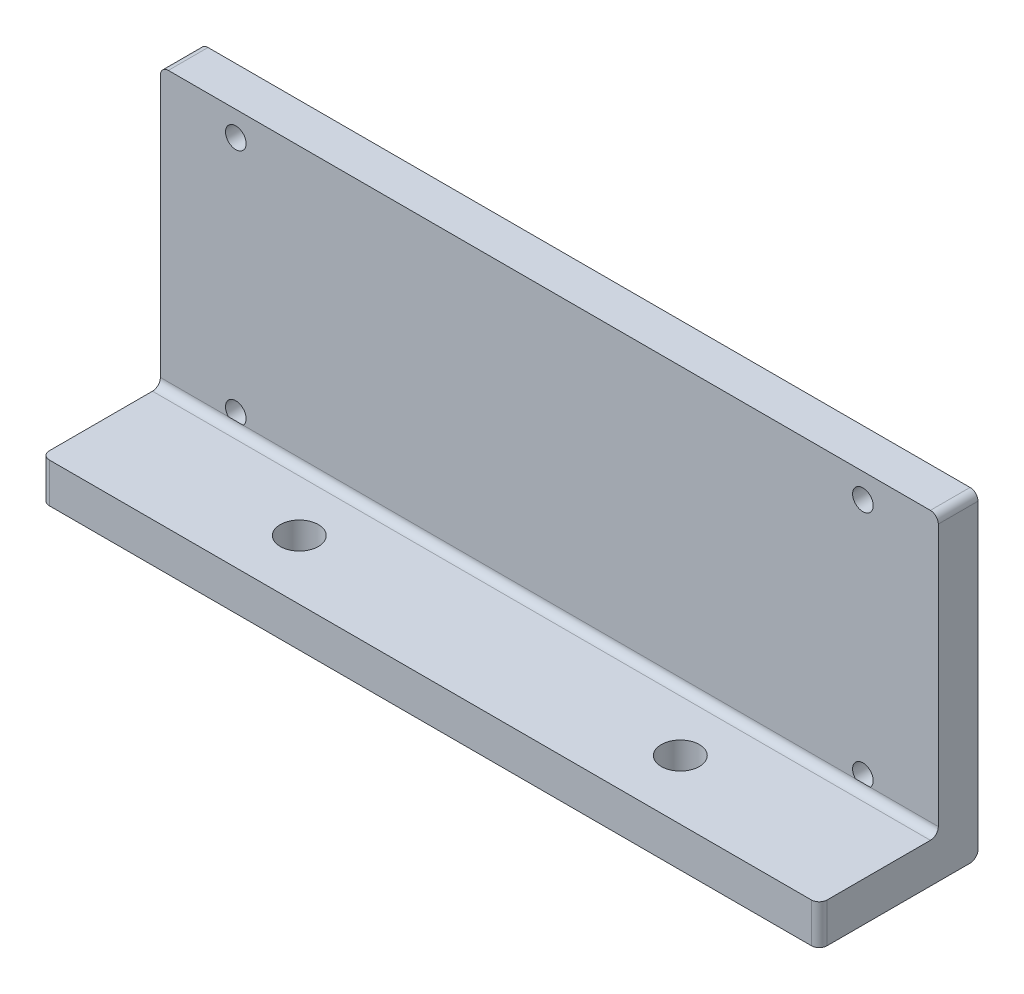
SolidWorks part; units mm, degrees
material "6061-T6 (SS)"
ref_plane "Front Plane" through (0, 0, 0) normal (0, 0, 1) x (1, 0, 0)
ref_plane "Top Plane" through (0, 0, 0) normal (0, 1, 0) x (1, 0, 0)
ref_plane "Right Plane" through (0, 0, 0) normal (1, 0, 0) x (0, 0, -1)
sketch "Sketch1" plane through (0, 0, 0) normal (0, 1, 0) x (1, 0, 0)
  line L1 (-49, -10) -> (49, -10)
  line L2 (-49, -10) -> (-49, 10)
  line L3 (-49, 10) -> (49, 10)
  line L4 (49, -10) -> (49, 10)
  line L5 (-49, -10) -> (49, 10) construction
  line L6 (-49, 10) -> (49, -10) construction
  point P0 (0, 0)
  dimension "D1" = 98
  dimension "D2" = 20
extrude "Boss-Extrude1" add sketch "Sketch1" along normal blind 5
sketch "Sketch2" plane through (0, 5, 0) normal (0, 1, 0) x (1, 0, 0)
  line L0 (-49, 10) -> (-49, -10) construction
  line L1 (49, 10) -> (-49, 10)
  line L2 (49, 10) -> (49, 5)
  line L3 (49, 5) -> (-49, 5)
  line L4 (-49, 10) -> (-49, 5)
  dimension "D1" = 5
extrude "Boss-Extrude2" add sketch "Sketch2" along normal blind 35
sketch "Sketch3" plane through (0, 0, -5) normal (0, 0, 1) x (1, 0, 0)
  line L0 (-49, 40) -> (49, 40) construction
  line L1 (-39.5, 36.9041) -> (39.5, 6.9041) construction
  line L2 (-39.5, 6.9041) -> (39.5, 36.9041) construction
  line L3 (-49, 5) -> (49, 5) construction
  circle A0 centre (-39.5, 6.9041) radius 0.8
  circle A1 centre (-39.5, 36.9041) radius 0.8
  circle A2 centre (39.5, 36.9041) radius 0.8
  circle A3 centre (39.5, 6.9041) radius 0.8
  point P12 (0, 21.9041)
  dimension "D1" = 16.9041
fillet "Fillet1" radius 1 6 edges at (0, 0, -10) (0, 5, -5) (49, 2.5, 10) (-49, 40, -7.5) (49, 40, -7.5) (-49, 2.5, 10)
sketch "Sketch4" plane through (0, 5, 0) normal (0, 1, 0) x (1, 0, 0)
  line L0 (-49, -2.5) -> (49, -2.5) construction
  line L1 (-49, 4) -> (-49, -9) construction
  line L2 (49, -9) -> (49, 4) construction
  line L3 (-48, -10) -> (48, -10) construction
  line L5 (0, -2.75) -> (0, 2.75) construction
  circle A0 centre (-24, -2.5) radius 1
  circle A2 centre (24, -2.5) radius 1
  dimension "D1" = 25
  dimension "D2" = 7.5
hole_wizard "M2 Clearance Hole1" positions "3DSketch1" profile "Sketch5" hole size "M2" standard "ANSI Metric"
sketch3d "3DSketch1"
  point P0 (39.5, 36.9041, -5)
  point P3 (39.5, 6.9041, -5)
  point P6 (-39.5, 36.9041, -5)
  point P9 (-39.5, 6.9041, -5)
sketch "Sketch5" plane through (39.5, 36.9041, -5) normal (1, 0, 0) x (0, -1, 0)
  line L0 (0, 0) -> (0, 5)
  line L1 (0, 5) -> (1.3, 5)
  line L2 (1.3, 5) -> (1.3, 0)
  line L5 (1.3, 0) -> (0, 0)
  line L11 (0, -6.35) -> (0, 107.95) construction
  dimension "Thru Hole Dia." = 2.6
  dimension "Thru Hole Depth" = 5
hole_wizard "M4 Clearance Hole1" positions "3DSketch2" profile "Sketch6" hole size "M4" standard "ANSI Metric" end condition through all
sketch3d "3DSketch2"
  point P0 (-24, 5, 2.5)
  point P3 (24, 5, 2.5)
sketch "Sketch6" plane through (-24, 5, 2.5) normal (1, 0, 0) x (0, 0, 1)
  line L0 (0, 0) -> (0, 5)
  line L1 (0, 5) -> (2.4, 5)
  line L2 (2.4, 5) -> (2.4, 0)
  line L5 (2.4, 0) -> (0, 0)
  line L11 (0, -6.35) -> (0, 107.95) construction
  dimension "Thru Hole Dia." = 4.8
  dimension "Thru Hole Depth" = 5
